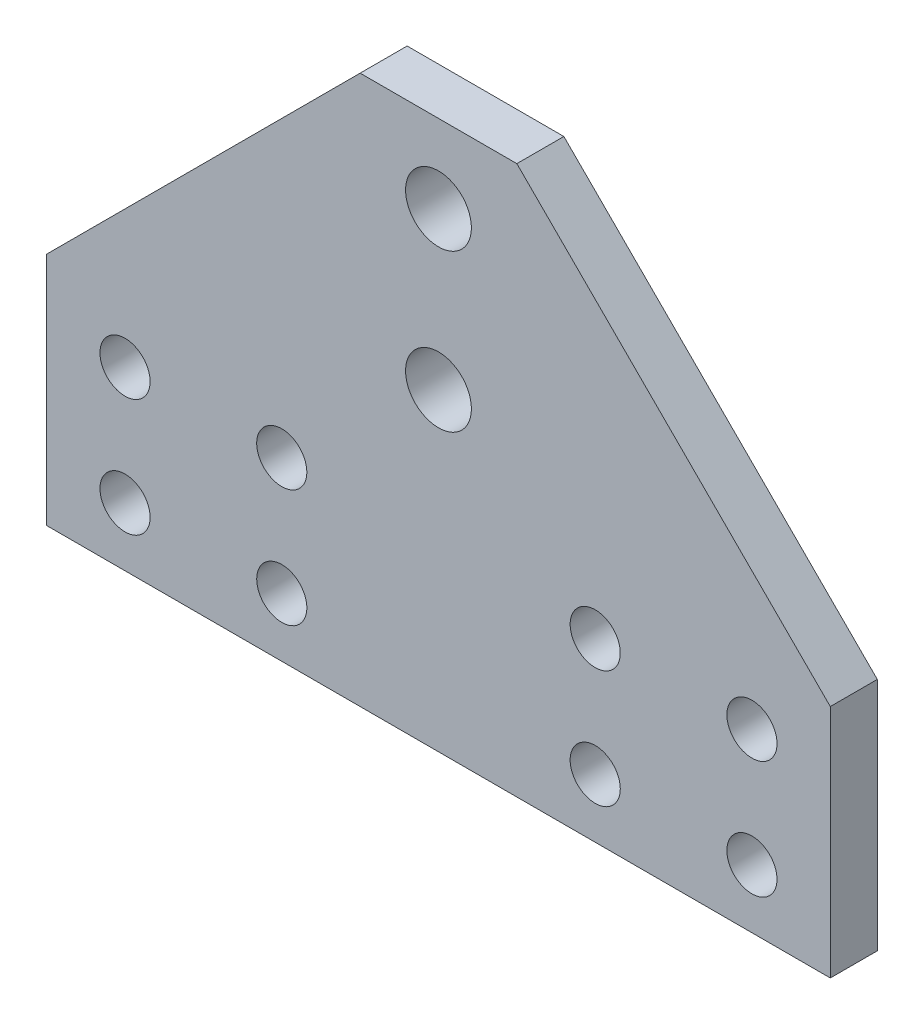
SolidWorks part; units mm, degrees
ref_plane "前视基准面" through (0, 0, 0) normal (0, 0, 1) x (1, 0, 0)
ref_plane "上视基准面" through (0, 0, 0) normal (0, 1, 0) x (1, 0, 0)
ref_plane "右视基准面" through (0, 0, 0) normal (1, 0, 0) x (0, 0, -1)
other "Configuration Table"
sketch "草图1" plane through (0, 0, 0) normal (0, 0, 1) x (1, 0, 0)
  line L0 (0, 0) -> (10, 0)
  line L1 (10, 0) -> (30, -20)
  line L2 (30, -20) -> (30, -35)
  line L3 (30, -35) -> (-20, -35)
  line L4 (-20, -35) -> (-20, -20)
  line L5 (-20, -20) -> (0, 0)
  line L6 (5, 0) -> (5, -35) construction
  point P3 (0, 0)
  dimension "D1" = 10
  dimension "D2" = 15
  dimension "D3" = 50
  dimension "D4" = 20
extrude "凸台-拉伸1" add sketch "草图1" along normal blind 3
sketch "草图2" plane through (0, 0, 3) normal (0, 0, 1) x (1, 0, 0)
  line L0 (5, 0) -> (5, -35) construction
  line L1 (10, 0) -> (0, 0) construction
  line L2 (-20, -35) -> (30, -35) construction
  line L3 (30, -27.5) -> (-20, -27.5) construction
  line L4 (30, -35) -> (30, -20) construction
  line L5 (-20, -20) -> (-20, -35) construction
  line L6 (-10, -35) -> (-10, -27.5) construction
  line L7 (20, -35) -> (20, -27.5) construction
  circle A0 centre (-15, -31.25) radius 1.6
  circle A1 centre (-5, -31.25) radius 1.6
  circle A2 centre (-5, -23.75) radius 1.6
  circle A3 centre (-15, -23.75) radius 1.6
  circle A4 centre (25, -23.75) radius 1.6
  circle A5 centre (15, -23.75) radius 1.6
  circle A6 centre (15, -31.25) radius 1.6
  circle A7 centre (25, -31.25) radius 1.6
  circle A8 centre (5, -5) radius 2.1
  circle A9 centre (5, -15) radius 2.1
  dimension "D1" = 3.2
  dimension "D5" = 4.2
  dimension "D7" = 4.2
  dimension "D2" = 5
  dimension "D3" = 3.75
  dimension "D4" = 10
  dimension "D6" = 5
  dimension "D8" = 10
extrude "切除-拉伸1" cut sketch "草图2" against normal through all
